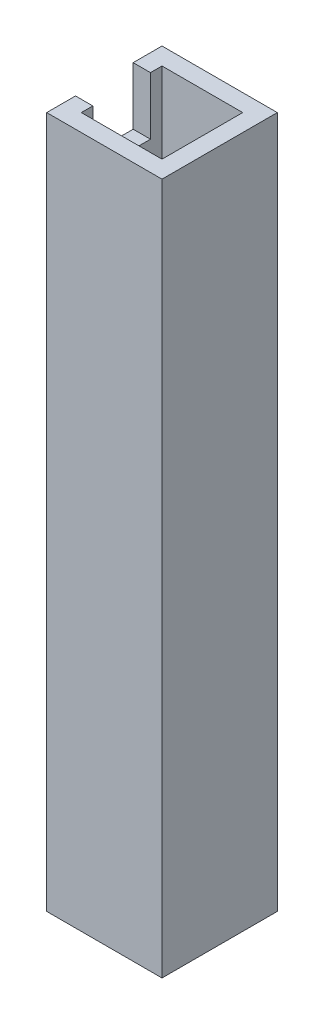
SolidWorks part; units mm, degrees
ref_plane "Front Plane" through (0, 0, 0) normal (0, 0, 1) x (1, 0, 0)
ref_plane "Top Plane" through (0, 0, 0) normal (0, 1, 0) x (1, 0, 0)
ref_plane "Right Plane" through (0, 0, 0) normal (1, 0, 0) x (0, 0, -1)
sketch "Sketch1" plane through (0, 0, 0) normal (0, 1, 0) x (1, 0, 0)
  line L1 (-8.0734, 5.0153) -> (11.9266, 5.0153)
  line L2 (-8.0734, 5.0153) -> (-8.0734, -14.9847)
  line L3 (-8.0734, -14.9847) -> (11.9266, -14.9847)
  line L4 (11.9266, 5.0153) -> (11.9266, -14.9847)
  dimension "D1" = 20
  dimension "D2" = 20
extrude "Boss-Extrude1" add sketch "Sketch1" along normal blind 120
shell "Shell1" thickness 3
sketch "Sketch2" plane through (-8.0734, 0, 0) normal (-1, 0, 0) x (0, 0, 1)
  line L0 (-5.0153, 120) -> (14.9847, 120) construction
  line L1 (-0.0153, 120) -> (9.9847, 120)
  line L2 (-0.0153, 120) -> (-0.0153, 110)
  line L3 (-0.0153, 110) -> (9.9847, 110)
  line L4 (9.9847, 120) -> (9.9847, 110)
  line L5 (14.9847, 120) -> (14.9847, 0) construction
  dimension "D1" = 10
  dimension "D2" = 10
  dimension "D3" = 5
extrude "Cut-Extrude1" cut sketch "Sketch2" against normal blind 3
